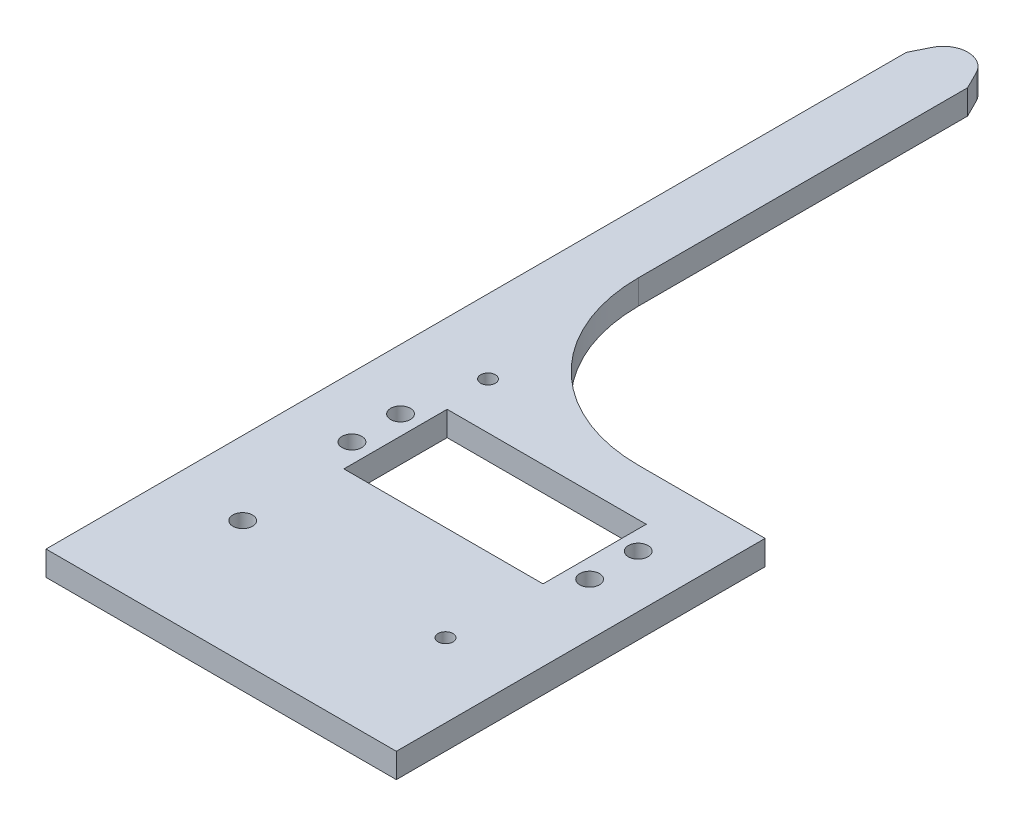
SolidWorks part; units mm, degrees
ref_plane "Front Plane" through (0, 0, 0) normal (0, 0, 1) x (1, 0, 0)
ref_plane "Top Plane" through (0, 0, 0) normal (0, 1, 0) x (1, 0, 0)
ref_plane "Right Plane" through (0, 0, 0) normal (1, 0, 0) x (0, 0, -1)
sketch "Sketch1" plane through (0, 0, 0) normal (0, 1, 0) x (1, 0, 0)
  line L0 (0, 48) -> (0, 33)
  line L1 (-45.4667, 13.2678) -> (5.0067, 13.2678)
  line L2 (-45.4667, 13.2678) -> (-45.4667, -47.4725)
  line L3 (-45.4667, -47.4725) -> (5.0067, -47.4725)
  line L4 (5.0067, 13.2678) -> (5.0067, -47.4725)
  line L5 (-45.4667, -33) -> (25.7862, -33)
  line L6 (-45.4667, -33) -> (-45.4667, -107.9997)
  line L7 (-45.4667, -107.9997) -> (25.7862, -107.9997)
  line L8 (25.7862, -33) -> (25.7862, -107.9997)
  line L9 (0, -33) -> (0, -48)
  line L10 (-45.46, 66.9743) -> (-39.23, 79.4343)
  line L11 (-33, 0) -> (-45.46, 0)
  line L12 (-33, 0) -> (-33, 66.9743)
  line L13 (-33, 66.9743) -> (-45.46, 66.9743)
  line L14 (-45.46, 0) -> (-45.46, 66.9743)
  line L15 (-33, 0) -> (-45.46, 66.9743) construction
  line L16 (-33, 66.9743) -> (-45.46, 0) construction
  line L17 (-39.23, 79.4343) -> (-33, 66.9743)
  circle A0 centre (0, 0) radius 33
  circle A1 centre (0, 0) radius 48
  point P20 (-39.23, 33.4871)
  dimension "D1" = 66
  dimension "D2" = 96
  dimension "D5" = 12.46
extrude "Boss-Extrude1" add sketch "Sketch1" along normal mid plane 5
sketch "Sketch2" plane through (0, 2.5, 0) normal (0, 1, 0) x (1, 0, 0)
  line L1 (-29.2862, -42.5955) -> (9.7138, -42.5955)
  line L2 (-29.2862, -42.5955) -> (-29.2862, -61.5955)
  line L3 (-29.2862, -61.5955) -> (9.7138, -61.5955)
  line L4 (9.7138, -42.5955) -> (9.7138, -61.5955)
  dimension "D1" = 39
  dimension "D2" = 19
extrude "Cut-Extrude2" cut sketch "Sketch2" against normal through all
sketch "Sketch6" plane through (0, 2.5, 0) normal (0, 1, 0) x (1, 0, 0)
  line L0 (-9.7862, -61.5955) -> (-9.7862, -104.4039) construction
  line L1 (-29.2862, -61.5955) -> (9.7138, -61.5955) construction
  line L2 (-9.7862, -82.9997) -> (25.7862, -82.9997) construction
  line L3 (25.7862, -33) -> (25.7862, -107.9997) construction
  line L4 (25.7862, -82.9997) -> (-45.4667, -82.9997) construction
  line L5 (-45.4667, 13.2678) -> (-45.4667, -107.9997) construction
  line L6 (9.7138, -42.5955) -> (-29.2862, -42.5955) construction
  line L7 (-45.4667, -107.9997) -> (25.7862, -107.9997) construction
  circle A0 centre (10.7862, -82.9997) radius 1.5
  circle A1 centre (-30.4667, -82.9997) radius 2
  circle A2 centre (-30.4667, -33.0955) radius 1.5
  dimension "D1" = 3
  dimension "D2" = 15
  dimension "D3" = 4
  dimension "D5" = 3
  dimension "D6" = 15
  dimension "D8" = 9.5
  dimension "D9" = 25
  dimension "D4" = 15
  dimension "D7" = 25
extrude "Cut-Extrude11" cut sketch "Sketch6" against normal through all
sketch "Sketch8" plane through (0, 2.5, 0) normal (0, 1, 0) x (1, 0, 0)
  line L1 (-29.2862, -61.5955) -> (9.8785, -61.5955)
  line L2 (-29.2862, -61.5955) -> (-29.2862, -63.5955)
  line L3 (-29.2862, -63.5955) -> (9.8785, -63.5955)
  line L4 (9.8785, -61.5955) -> (9.8785, -63.5955)
  dimension "D1" = 2
extrude "Cut-Extrude12" cut sketch "Sketch8" against normal blind 10
sketch "Sketch9" plane through (0, 2.5, 0) normal (0, 1, 0) x (1, 0, 0)
  line L1 (-29.2862, -42.5955) -> (11.2138, -42.5955)
  line L2 (-29.2862, -42.5955) -> (-29.2862, -63.5955)
  line L3 (-29.2862, -63.5955) -> (11.2138, -63.5955)
  line L4 (11.2138, -42.5955) -> (11.2138, -63.5955)
  dimension "D1" = 40.5
  dimension "D2" = 21
extrude "Cut-Extrude14" cut sketch "Sketch9" against normal blind 10
sketch "Sketch10" plane through (0, 2.5, 0) normal (0, 1, 0) x (1, 0, 0)
  line L0 (-29.2862, -42.5955) -> (-29.2862, -48.1555)
  line L1 (-29.2862, -42.5955) -> (-29.2862, -63.5955) construction
  line L2 (-29.2862, -48.1555) -> (-33.2062, -48.1555)
  line L3 (11.2138, -53.0955) -> (-29.2862, -53.0955)
  line L4 (11.2138, -63.5955) -> (11.2138, -42.5955) construction
  line L5 (-9.0362, -42.5955) -> (-9.0362, -63.5955)
  line L6 (11.2138, -42.5955) -> (-29.2862, -42.5955) construction
  line L7 (-29.2862, -63.5955) -> (11.2138, -63.5955) construction
  circle A0 centre (-33.2062, -48.1555) radius 2
  circle A1 centre (-33.2062, -58.0355) radius 2
  circle A2 centre (15.1338, -58.0355) radius 2
  circle A3 centre (15.1338, -48.1555) radius 2
  dimension "D3" = 4
  dimension "D1" = 5.56
  dimension "D2" = 3.92
extrude "Cut-Extrude16" cut sketch "Sketch10" against normal blind 10
sketch "Sketch13" plane through (0, 2.5, 0) normal (0, 1, 0) x (1, 0, 0)
sketch "Sketch14" plane through (0, 2.5, 0) normal (0, 1, 0) x (1, 0, 0)
  line L1 (28.5157, 51.9634) -> (-33, 51.9634)
  line L2 (28.5157, 51.9634) -> (28.5157, 0)
  line L3 (28.5157, 0) -> (-33, 0)
  line L4 (-33, 51.9634) -> (-33, 0)
  line L5 (28.5157, 51.9634) -> (-33, 0) construction
  line L6 (28.5157, 0) -> (-33, 51.9634) construction
  point P4 (-2.2421, 25.9817)
extrude "Cut-Extrude19" cut sketch "Sketch14" against normal blind 10
fillet "Fillet4" radius 5 1 edges at (-39.23, 0, -79.4343)
